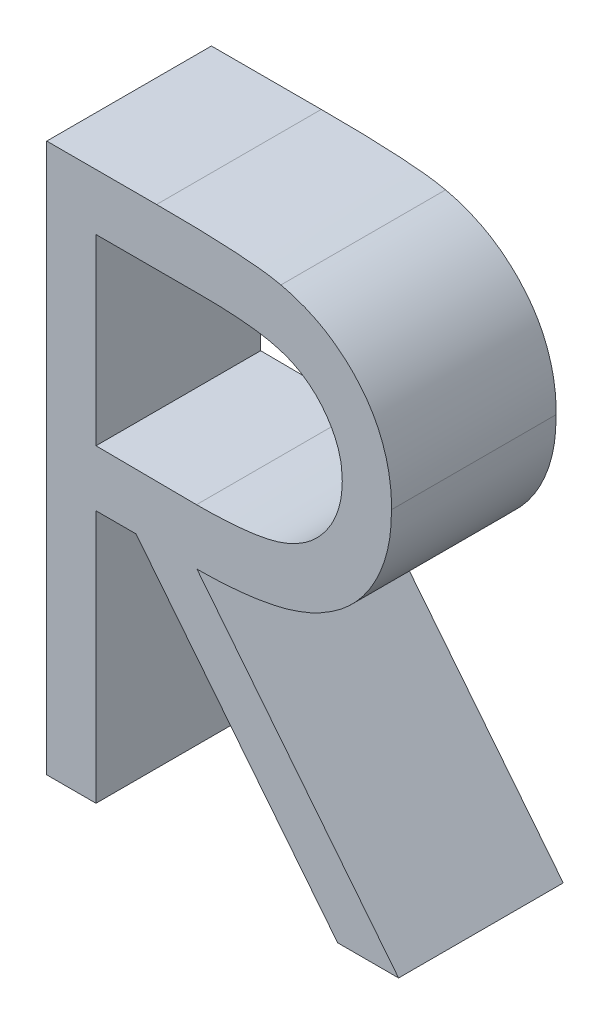
SolidWorks part; units mm, degrees
ref_plane "Plan de face" through (0, 0, 0) normal (0, 0, 1) x (1, 0, 0)
ref_plane "Plan de dessus" through (0, 0, 0) normal (0, 1, 0) x (1, 0, 0)
ref_plane "Plan de droite" through (0, 0, 0) normal (1, 0, 0) x (0, 0, -1)
sketch "Esquisse1" plane through (0, 0, 0) normal (0, 0, 1) x (1, 0, 0)
  text T0 "R" font "Century Gothic" height 5
extrude "Boss.-Extru.1" add sketch "Esquisse1" along normal blind 1.5
